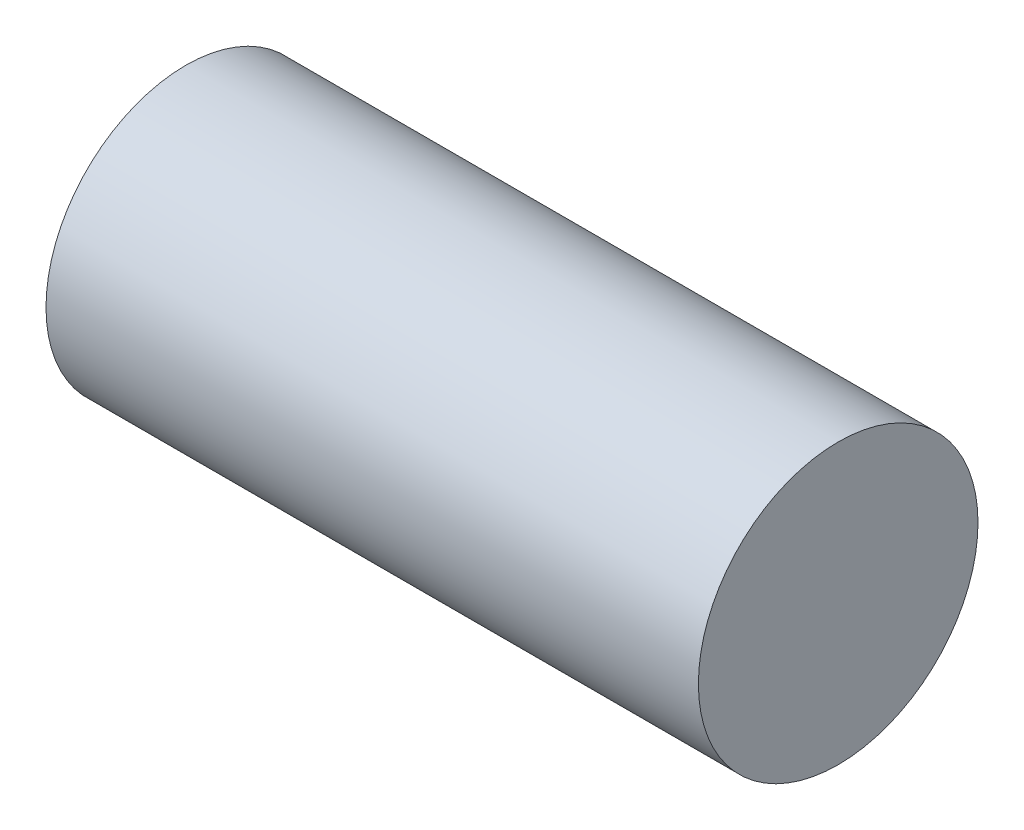
SolidWorks part; units mm, degrees
ref_plane "Front Plane" through (0, 0, 0) normal (0, 0, 1) x (1, 0, 0)
ref_plane "Top Plane" through (0, 0, 0) normal (0, 1, 0) x (1, 0, 0)
ref_plane "Right Plane" through (0, 0, 0) normal (1, 0, 0) x (0, 0, -1)
sketch "Sketch1" plane through (0, 0, 0) normal (0, 0, 1) x (1, 0, 0)
  line L0 (0, 0) -> (-3.5, 0)
  line L1 (-3.5, 0) -> (-3.5, 1.5)
  line L2 (-3.5, 1.5) -> (0, 1.5)
  line L3 (0, 1.5) -> (0, 0)
  line L5 (0, 0) -> (1.2079, 0) construction
  dimension "D1" = 3.5
  dimension "D2" = 1.5
revolve "Revolve5" add sketch "Sketch1" angle 360 about L5
mirror "Mirror1" about plane through (0, 0, 0) normal (1, 0, 0) of "Revolve5"
